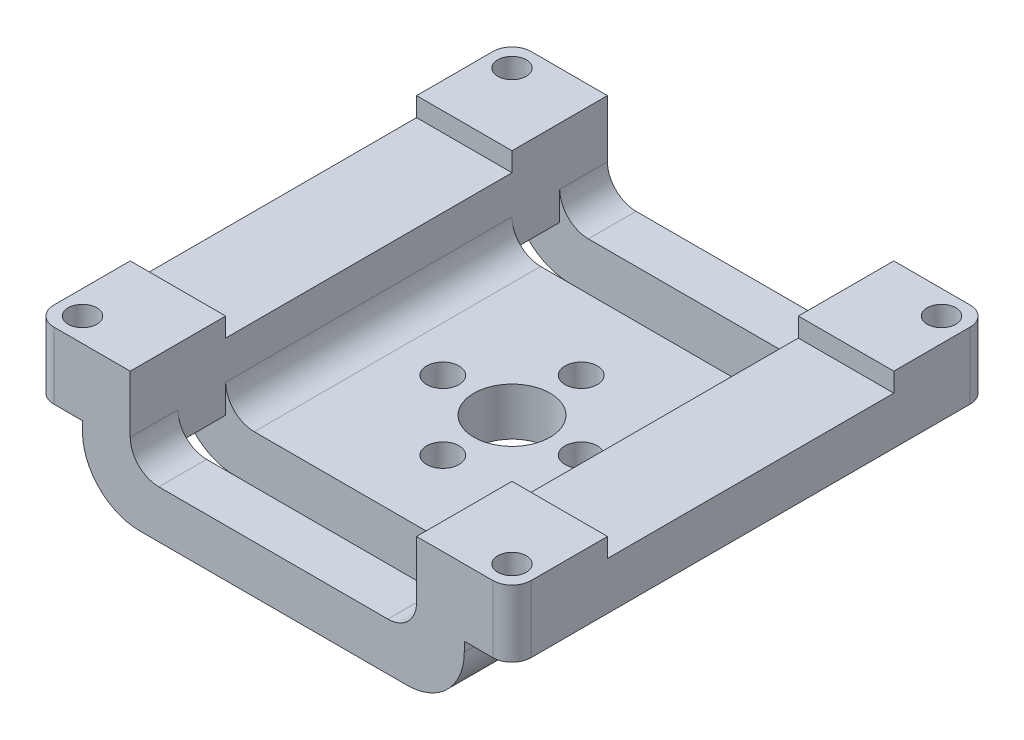
SolidWorks part; units mm, degrees
ref_plane "前视基准面" through (0, 0, 0) normal (0, 0, 1) x (1, 0, 0)
ref_plane "上视基准面" through (0, 0, 0) normal (0, 1, 0) x (1, 0, 0)
ref_plane "右视基准面" through (0, 0, 0) normal (1, 0, 0) x (0, 0, -1)
sketch "草图1" plane through (0, 0, 0) normal (0, 0, 1) x (1, 0, 0)
  line L0 (-45, 4.3806) -> (-35, 4.3806)
  line L1 (-35, 4.3806) -> (-35, -2.6194)
  line L2 (-35, -2.6194) -> (-5, -2.6194)
  line L3 (-5, -2.6194) -> (-5, 4.3806)
  line L4 (-5, 4.3806) -> (5, 4.3806)
  line L5 (5, 4.3806) -> (5, -0.6194)
  line L6 (5, -0.6194) -> (0, -0.6194)
  line L7 (0, -0.6194) -> (0, -7.6194)
  line L8 (0, -7.6194) -> (-40, -7.6194)
  line L9 (-40, -7.6194) -> (-40, -0.6194)
  line L10 (-40, -0.6194) -> (-45, -0.6194)
  line L11 (-45, -0.6194) -> (-45, 4.3806)
  point P12 (0, 0)
  dimension "D1" = 5
  dimension "D2" = 5
  dimension "D3" = 5
  dimension "D4" = 5
  dimension "D5" = 5
  dimension "D6" = 30
  dimension "D7" = 7
  dimension "D8" = 7
  dimension "D9" = 50
  dimension "D10" = 10
extrude "凸台-拉伸1" add sketch "草图1" along normal blind 50
sketch "草图2" plane through (0, -2.6194, 0) normal (0, 1, 0) x (1, 0, 0)
  circle A0 centre (-20, -25) radius 4
  circle A1 centre (-20, -17.75) radius 1.7
  circle A2 centre (-12.75, -25) radius 1.7
  circle A3 centre (-20, -32.25) radius 1.7
  circle A4 centre (-27.25, -25) radius 1.7
  point P19 (-20, -25)
  dimension "D1" = 7.25
  dimension "D2" = 4
extrude "切除-拉伸1" cut sketch "草图2" against normal blind 50
sketch "草图3" plane through (0, 4.3806, 0) normal (0, 1, 0) x (1, 0, 0)
  line L0 (-5, -50) -> (-5, -40)
  line L1 (-5, -50) -> (-5, 0) construction
  line L2 (-5, -40) -> (5, -40)
  line L3 (5, -50) -> (5, 0) construction
  line L4 (5, -40) -> (5, -50)
  line L5 (5, -50) -> (-5, -50)
  line L7 (-35, -40) -> (-35, -50)
  line L8 (-45, -40) -> (-35, -40)
  line L9 (-35, -50) -> (-45, -50)
  line L10 (-45, -50) -> (-45, -40)
  line L11 (-35, -10) -> (-45, -10)
  line L12 (-35, 0) -> (-35, -10)
  line L13 (-45, -10) -> (-45, 0)
  line L14 (-45, 0) -> (-35, 0)
  line L15 (-5, -10) -> (-5, 0)
  line L16 (5, -10) -> (-5, -10)
  line L17 (-5, 0) -> (5, 0)
  line L18 (5, 0) -> (5, -10)
  point P27 (-20, -25)
  dimension "D1" = 4
extrude "凸台-拉伸2" add sketch "草图3" along normal blind 2
fillet "圆角1" radius 6 1 edges at (-40, -7.6194, 25)
fillet "圆角2" radius 6 1 edges at (0, -7.6194, 25)
fillet "圆角3" radius 3 1 edges at (-5, -2.6194, 25)
fillet "圆角4" radius 3 1 edges at (-35, -2.6194, 25)
sketch "草图4" plane through (0, -0.6194, 0) normal (0, -1, 0) x (1, 0, 0)
  line L0 (5, 50) -> (2.5, 50)
  line L1 (0, 50) -> (5, 50) construction
sketch "草图5" plane through (0, -0.6194, 0) normal (0, -1, 0) x (1, 0, 0)
  line L0 (5, 50) -> (2.5, 50) construction
  line L1 (5, 50) -> (5, 0) construction
  line L2 (5, 25) -> (-45, 25) construction
  line L3 (-45, 50) -> (-45, 0) construction
  line L4 (-20, 25) -> (-20, 36.4253) construction
  circle A0 centre (2.5, 47.5) radius 1.5
  circle A1 centre (2.5, 2.5) radius 1.5
  circle A2 centre (-42.5, 2.5) radius 1.5
  circle A3 centre (-42.5, 47.5) radius 1.5
  dimension "D1" = 2.5
  dimension "D2" = 2.5
extrude "切除-拉伸2" cut sketch "草图5" against normal blind 23
fillet "圆角5" radius 2 1 edges at (5, 2.8806, 50)
fillet "圆角6" radius 2 1 edges at (5, 2.8806, 0)
fillet "圆角7" radius 2 1 edges at (-45, 2.8806, 0)
fillet "圆角8" radius 2 1 edges at (-45, 2.8806, 50)
sketch "草图7" plane through (0, -7.6194, 0) normal (0, -1, 0) x (1, 0, 0)
  line L2 (-42.4691, 45) -> (1.8886, 45)
  line L3 (1.8886, 45) -> (1.8886, 40)
  line L4 (1.8886, 40) -> (-42.4691, 40)
  line L5 (-42.4691, 40) -> (-42.4691, 45)
  line L6 (-34, 50) -> (-6, 50) construction
  line L7 (-42.4691, 10) -> (-42.4691, 5)
  line L8 (1.8886, 10) -> (-42.4691, 10)
  line L9 (1.8886, 5) -> (1.8886, 10)
  line L10 (-42.4691, 5) -> (1.8886, 5)
  point P8 (-42.4691, 38.0472)
  point P9 (1.8886, 42.5)
  dimension "D1" = 5
  dimension "D2" = 7.5
extrude "切除-拉伸4" cut sketch "草图7" against normal blind 5
sketch "草图8" plane through (0, 6.3806, 0) normal (0, 1, 0) x (1, 0, 0)
  line L0 (-8, -40) -> (-5, -40)
  line L1 (-5, -40) -> (-5, -45)
  line L2 (-5, -40) -> (-5, -50) construction
  line L3 (-5, -45) -> (-35, -45)
  line L4 (-35, -50) -> (-35, -40) construction
  line L5 (-35, -45) -> (-35, -40)
  line L6 (-35, -40) -> (-8, -40)
  line L7 (-32, -25) -> (-29.6459, -25)
  line L8 (-32, -10) -> (-32, -40) construction
  line L9 (-35, -10) -> (-8, -10)
  line L10 (-35, -5) -> (-35, -10)
  line L11 (-5, -5) -> (-35, -5)
  line L12 (-5, -10) -> (-5, -5)
  line L13 (-8, -10) -> (-5, -10)
  line M6 (-35, -50) -> (-35, -40)
extrude "切除-拉伸5" cut sketch "草图8" against normal blind 31 contours L6 L3 L1 L0 M6 | L9 L13 L12 L11 L10
